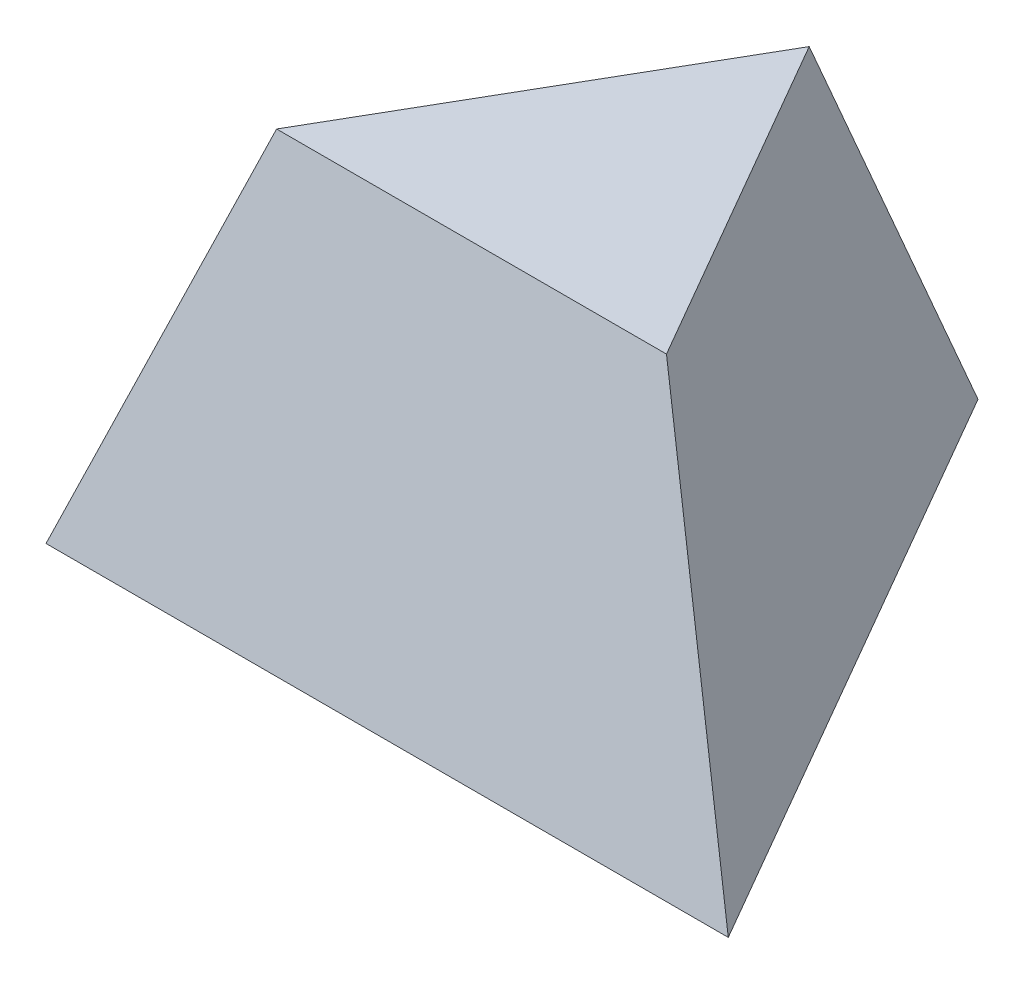
SolidWorks part; units mm, degrees
ref_plane "Front Plane" through (0, 0, 0) normal (0, 0, 1) x (1, 0, 0)
ref_plane "Top Plane" through (0, 0, 0) normal (0, 1, 0) x (1, 0, 0)
ref_plane "Right Plane" through (0, 0, 0) normal (1, 0, 0) x (0, 0, -1)
sketch "Sketch1" plane through (0, 0, 0) normal (0, 1, 0) x (1, 0, 0)
  line L0 (0, 102.6529) -> (-88.9, -51.3264)
  line L1 (-88.9, -51.3264) -> (88.9, -51.3264)
  line L2 (88.9, -51.3264) -> (0, 102.6529)
  line L3 (0, 0) -> (-88.9, -51.3264) construction
  line L4 (0, 0) -> (0, 102.6529) construction
  dimension "D1" = 177.8
extrude "Boss-Extrude1" add sketch "Sketch1" along normal blind 101.6
sketch "Sketch2" plane through (0, 101.6, 0) normal (0, 1, 0) x (1, 0, 0)
  line L0 (0, 58.6588) -> (-50.8, -29.3294)
  line L1 (-50.8, -29.3294) -> (50.8, -29.3294)
  line L2 (50.8, -29.3294) -> (0, 58.6588)
  line L3 (0, 0) -> (0, 58.6588) construction
  line L4 (0, 0) -> (-50.8, -29.3294) construction
  line L5 (0, 0) -> (50.8, -29.3294) construction
  dimension "D1" = 101.6
ref_plane "Plane1" through (0, 10.6149, 49.0282) normal (0, -0.2116, -0.9774) x (-1, 0, 0)
ref_plane "Plane2" through (42.4597, 10.6149, -24.5141) normal (-0.8464, -0.2116, 0.4887) x (0.4832, 0.0803, 0.8718)
ref_plane "Plane3" through (-42.4597, 10.6149, -24.5141) normal (0.8464, -0.2116, 0.4887) x (0.4832, -0.0803, -0.8718)
sketch "Sketch3" plane through (-42.4597, 10.6149, -24.5141) normal (0.8464, -0.2116, 0.4887) x (0.4832, -0.0803, -0.8718)
  line L1 (-192.3382, -90.3155) -> (223.3753, -90.3155)
  line L2 (-192.3382, -90.3155) -> (-192.3382, 141.9362)
  line L3 (-192.3382, 141.9362) -> (223.3753, 141.9362)
  line L4 (223.3753, -90.3155) -> (223.3753, 141.9362)
  line L5 (-192.3382, -90.3155) -> (223.3753, 141.9362) construction
  line L6 (-192.3382, 141.9362) -> (223.3753, -90.3155) construction
  point P0 (15.5185, 25.8103)
extrude "Cut-Extrude1" cut sketch "Sketch3" against normal blind 152.4
sketch "Sketch4" plane through (0, 10.6149, 49.0282) normal (0, -0.2116, -0.9774) x (-1, 0, 0)
  line L1 (-158.3385, -86.1933) -> (171.9231, -86.1933)
  line L2 (-158.3385, -86.1933) -> (-158.3385, 171.3258)
  line L3 (-158.3385, 171.3258) -> (171.9231, 171.3258)
  line L4 (171.9231, -86.1933) -> (171.9231, 171.3258)
  line L5 (-158.3385, -86.1933) -> (171.9231, 171.3258) construction
  line L6 (-158.3385, 171.3258) -> (171.9231, -86.1933) construction
  point P0 (6.7923, 42.5663)
extrude "Cut-Extrude2" cut sketch "Sketch4" against normal blind 152.4
sketch "Sketch5" plane through (42.4597, 10.6149, -24.5141) normal (-0.8464, -0.2116, 0.4887) x (0.4832, 0.0803, 0.8718)
  line L1 (-136.6336, -55.6689) -> (167.4999, -55.6689)
  line L2 (-136.6336, -55.6689) -> (-136.6336, 154.4511)
  line L3 (-136.6336, 154.4511) -> (167.4999, 154.4511)
  line L4 (167.4999, -55.6689) -> (167.4999, 154.4511)
  line L5 (-136.6336, -55.6689) -> (167.4999, 154.4511) construction
  line L6 (-136.6336, 154.4511) -> (167.4999, -55.6689) construction
  point P0 (15.4332, 49.3911)
extrude "Cut-Extrude3" cut sketch "Sketch5" against normal blind 152.4
